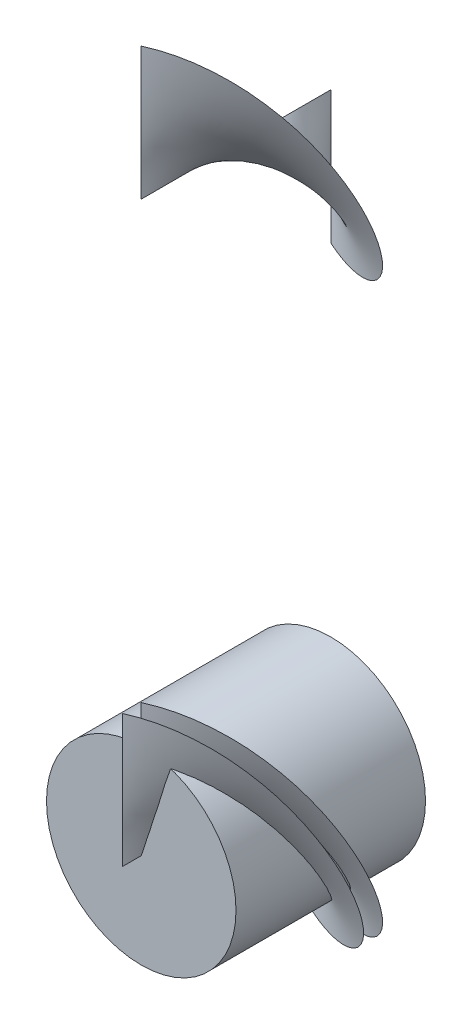
SolidWorks part; units mm, degrees
ref_plane "Front Plane" through (0, 0, 0) normal (0, 0, 1) x (1, 0, 0)
ref_plane "Top Plane" through (0, 0, 0) normal (0, 1, 0) x (1, 0, 0)
ref_plane "Right Plane" through (0, 0, 0) normal (1, 0, 0) x (0, 0, -1)
sketch "Sketch1" plane through (0, 0, 0) normal (0, 0, 1) x (1, 0, 0)
  circle A0 centre (0, 0) radius 50
extrude "Boss-Extrude1" add sketch "Sketch1" along normal blind 100
sketch "Sketch2" plane through (0, 0, 0) normal (0, 1, 0) x (1, 0, 0)
  line L0 (0, 0) -> (0, -100)
  line L1 (-50, -100) -> (50, -100) construction
sketch "Sketch3" plane through (0, 0, 0) normal (1, 0, 0) x (0, 0, -1)
  line L0 (-100, 0) -> (-100, 70)
  line L1 (-100, 50) -> (-100, -50) construction
surface "Surface-Sweep1" parameters "D0"=180
move or copy body "Body-Move/Copy1" bodies to move or copy 102 copy yes number of copies 1 translate (0, 300, 0) parameters "D1"=0, "D2"=300, "D3"=0
move or copy body "Body-Move/Copy2" bodies to move or copy 102 copy yes number of copies 1 translate (0, 0, 10) parameters "D1"=0, "D2"=0, "D3"=10
